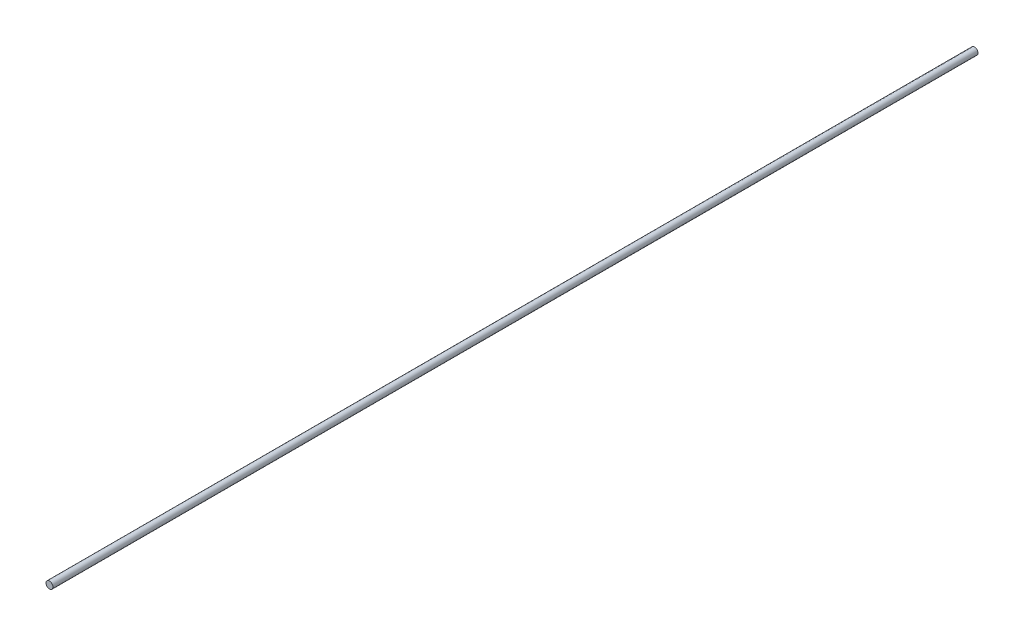
SolidWorks part; units mm, degrees
ref_plane "前视基准面" through (0, 0, 0) normal (0, 0, 1) x (1, 0, 0)
ref_plane "上视基准面" through (0, 0, 0) normal (0, 1, 0) x (1, 0, 0)
ref_plane "右视基准面" through (0, 0, 0) normal (1, 0, 0) x (0, 0, -1)
other "Configuration Table"
sketch "草图1" plane through (0, 0, 0) normal (0, 0, 1) x (1, 0, 0)
  circle A0 centre (0, 0) radius 1.5
extrude "凸台-拉伸1" add sketch "草图1" against normal blind 400
